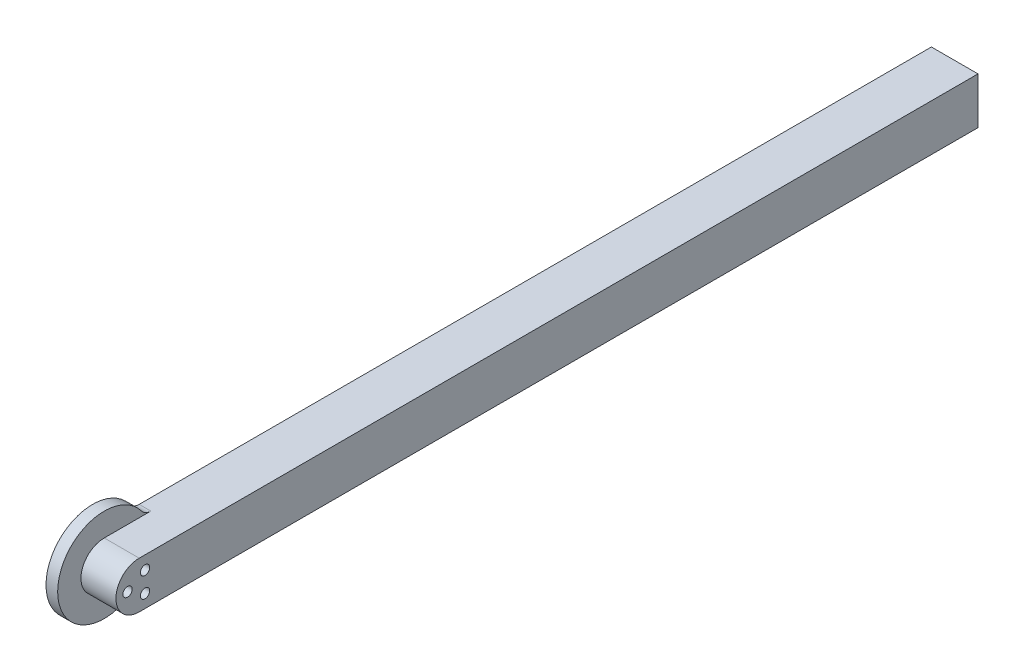
SolidWorks part; units mm, degrees
material "6061 Alloy"
ref_plane "Front Plane" through (0, 0, 0) normal (0, 0, 1) x (1, 0, 0)
ref_plane "Top Plane" through (0, 0, 0) normal (0, 1, 0) x (1, 0, 0)
ref_plane "Right Plane" through (0, 0, 0) normal (1, 0, 0) x (0, 0, -1)
sketch "Sketch1" plane through (0, 0, 0) normal (1, 0, 0) x (0, 0, -1)
  line L0 (-6.35, 0) -> (0, 0) construction
  line L1 (0, 0) -> (3.175, 5.4993) construction
  line L2 (0, 0) -> (3.175, -5.4993) construction
  line L3 (0, 12.7) -> (457.2, 12.7)
  line L4 (0, -12.7) -> (457.2, -12.7)
  line L5 (457.2, 12.7) -> (457.2, -12.7)
  circle A0 centre (3.175, 5.4993) radius 2.5527
  circle A1 centre (-6.35, 0) radius 2.5527
  circle A2 centre (3.175, -5.4993) radius 2.5527
  arc A3 (0, -12.7) -> (0, 12.7) centre (0, 0) cw
  dimension "D1" = 5.1054
  dimension "D5" = 12.7
  dimension "D2" = 6.35
  dimension "D3" = 120
  dimension "D4" = 120
  dimension "D6" = 457.2
extrude "Boss-Extrude1" add sketch "Sketch1" along normal mid plane 25.4
sketch "Sketch3" plane through (-12.7, 0, 0) normal (-1, 0, 0) x (0, 0, 1)
  circle A0 centre (0, 0) radius 25.4
  dimension "D1" = 50.8
extrude "Boss-Extrude2" add sketch "Sketch3" against normal blind 6.35
sketch "Sketch4" plane through (-6.35, 0, 0) normal (1, 0, 0) x (0, 0, -1)
  circle A0 centre (3.175, 5.4993) radius 2.5527 construction
  circle A1 centre (3.175, -5.4993) radius 2.5527 construction
  circle A2 centre (-6.35, 0) radius 2.5527 construction
  circle A3 centre (3.175, 5.4993) radius 2.5527
  circle A4 centre (3.175, -5.4993) radius 2.5527
  circle A5 centre (-6.35, 0) radius 2.5527
extrude "Cut-Extrude1" cut sketch "Sketch4" against normal through all
fillet "Fillet1" radius 6.35 2 edges at (-9.525, -12.7, -21.997) (-9.525, 12.7, -21.997)
